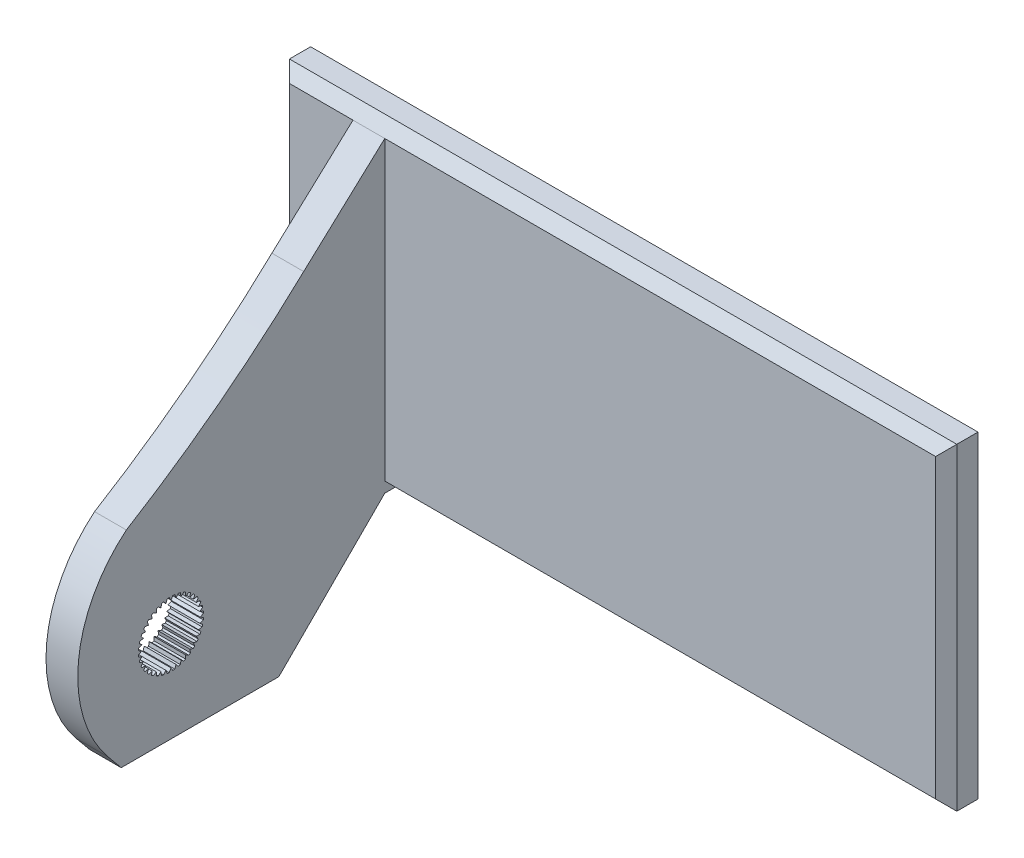
SolidWorks part; units mm, degrees
ref_plane "Front Plane" through (0, 0, 0) normal (0, 0, 1) x (1, 0, 0)
ref_plane "Top Plane" through (0, 0, 0) normal (0, 1, 0) x (1, 0, 0)
ref_plane "Right Plane" through (0, 0, 0) normal (1, 0, 0) x (0, 0, -1)
sketch "Sketch2" plane through (0, 0, 0) normal (0, 0, 1) x (1, 0, 0)
  line L1 (-31.5, -15) -> (31.5, -15)
  line L2 (-31.5, -15) -> (-31.5, 15)
  line L3 (-31.5, 15) -> (31.5, 15)
  line L4 (31.5, -15) -> (31.5, 15)
  point P4 (0, 15)
  point P6 (-31.5, 0)
  dimension "D1" = 63
  dimension "D2" = 30
extrude "Boss-Extrude2" add sketch "Sketch2" along normal blind 3
sketch "Sketch6" plane through (0, 0, 3) normal (0, 0, 1) x (1, 0, 0)
  line L0 (31.5, 15) -> (-31.5, 15) construction
  line L1 (-24.5, 15) -> (-21.5, 15)
  line L2 (-24.5, 15) -> (-24.5, -15)
  line L3 (-24.5, -15) -> (-21.5, -15)
  line L4 (-21.5, 15) -> (-21.5, -15)
  line L5 (-31.5, -15) -> (31.5, -15) construction
  line L6 (-31.5, 15) -> (-31.5, -15) construction
  dimension "D1" = 3
  dimension "D2" = 7
extrude "Boss-Extrude5" add sketch "Sketch6" along normal blind 20
sketch "Sketch7" plane through (0, -15, 0) normal (0, -1, 0) x (1, 0, 0)
  line L0 (-31.5, 0) -> (31.5, 0) construction
  line L1 (-24.5, 23) -> (-21.5, 23)
  line L2 (-24.5, 23) -> (-24.5, 0)
  line L3 (-24.5, 0) -> (-21.5, 0)
  line L4 (-21.5, 23) -> (-21.5, 0)
  dimension "D1" = 3
extrude "Boss-Extrude6" add sketch "Sketch7" along normal blind 10
sketch "Sketch8" plane through (0, 0, 23) normal (0, 0, 1) x (1, 0, 0)
  line L6 (-24.5, 15) -> (-24.5, -25)
  line L7 (-24.5, -25) -> (-21.5, -25)
  line L8 (-21.5, -25) -> (-21.5, 15)
  line L11 (-21.5, 15) -> (-24.5, 15)
  line L12 (-24.5, 15) -> (-24.5, -25)
  line L13 (-24.5, -25) -> (-21.5, -25)
  line L14 (-21.5, -25) -> (-21.5, 15)
  line L17 (-21.5, 15) -> (-24.5, 15)
  dimension "D1" = 0
extrude "Boss-Extrude7" add sketch "Sketch8" along normal blind 15
sketch "Sketch9" plane through (-24.5, 0, 0) normal (-1, 0, 0) x (0, 0, 1)
  line L288 (25.551, -14.882) -> (25.5973, -14.8018) construction
  line L289 (25.5298, -14.7054) -> (25.4386, -14.7215) construction
  line L290 (25.5973, -14.8018) -> (25.6299, -14.7454) construction
  line L291 (25.5939, -14.6941) -> (25.5298, -14.7054) construction
  line L292 (25.4711, -15.0204) -> (25.551, -14.882) construction
  line L293 (25.4386, -14.7215) -> (25.2812, -14.7493) construction
  line L294 (25.279, -14.4066) -> (25.3013, -14.3454) construction
  line L295 (25.257, -14.3011) -> (25.1958, -14.3233) construction
  line L296 (25.2473, -14.4936) -> (25.279, -14.4066) construction
  line L297 (25.1958, -14.3233) -> (25.1088, -14.355) construction
  line L298 (25.1927, -14.6438) -> (25.2473, -14.4936) construction
  line L299 (25.1088, -14.355) -> (24.9586, -14.4097) construction
  line L300 (24.8569, -13.9725) -> (24.8005, -14.0051) construction
  line L301 (24.8969, -14.0726) -> (24.9082, -14.0084) construction
  line L302 (24.8005, -14.0051) -> (24.7203, -14.0514) construction
  line L303 (24.8808, -14.1638) -> (24.8969, -14.0726) construction
  line L304 (24.7203, -14.0514) -> (24.5819, -14.1313) construction
  line L305 (24.8531, -14.3211) -> (24.8808, -14.1638) construction
  line L306 (25.6799, -15.4397) -> (25.7826, -15.3173) construction
  line L307 (25.6998, -15.1397) -> (25.54, -15.1397) construction
  line L308 (25.8421, -15.2464) -> (25.884, -15.1965) construction
  line L309 (25.8575, -15.1397) -> (25.7924, -15.1397) construction
  line L310 (25.7826, -15.3173) -> (25.8421, -15.2464) construction
  line L311 (25.7924, -15.1397) -> (25.6998, -15.1397) construction
  line L312 (26.006, -15.7267) -> (26.0559, -15.6848) construction
  line L313 (26.0397, -15.6243) -> (25.9756, -15.613) construction
  line L314 (25.9351, -15.7862) -> (26.006, -15.7267) construction
  line L315 (25.9756, -15.613) -> (25.8843, -15.5969) construction
  line L316 (25.8126, -15.8889) -> (25.9351, -15.7862) construction
  line L317 (25.8843, -15.5969) -> (25.727, -15.5692) construction
  line L318 (25.8654, -16.3543) -> (26.0038, -16.2744) construction
  line L319 (25.9867, -16.0792) -> (25.8366, -16.0246) construction
  line L320 (26.0038, -16.2744) -> (26.084, -16.2281) construction
  line L321 (26.0738, -16.1109) -> (25.9867, -16.0792) construction
  line L322 (26.084, -16.2281) -> (26.1404, -16.1956) construction
  line L323 (26.1349, -16.1332) -> (26.0738, -16.1109) construction
  line L324 (26.1404, -16.6509) -> (26.084, -16.6183) construction
  line L325 (26.0738, -16.7355) -> (26.1349, -16.7133) construction
  line L326 (26.084, -16.6183) -> (26.0038, -16.572) construction
  line L327 (25.9867, -16.7672) -> (26.0738, -16.7355) construction
  line L328 (26.0038, -16.572) -> (25.8654, -16.4921) construction
  line L329 (25.8366, -16.8219) -> (25.9867, -16.7672) construction
  line L330 (25.9756, -17.2334) -> (26.0397, -17.2221) construction
  line L331 (26.0559, -17.1616) -> (26.006, -17.1198) construction
  line L332 (25.8843, -17.2495) -> (25.9756, -17.2334) construction
  line L333 (26.006, -17.1198) -> (25.9351, -17.0602) construction
  line L334 (25.727, -17.2773) -> (25.8843, -17.2495) construction
  line L335 (25.9351, -17.0602) -> (25.8126, -16.9575) construction
  line L336 (25.6998, -17.7067) -> (25.7924, -17.7067) construction
  line L337 (25.8421, -17.6001) -> (25.7826, -17.5291) construction
  line L338 (25.54, -17.7067) -> (25.6998, -17.7067) construction
  line L339 (25.7826, -17.5291) -> (25.6799, -17.4067) construction
  line L340 (25.8654, -16.4921) -> (25.7461, -16.4232) construction
  line L341 (25.7461, -16.4232) -> (25.8654, -16.3543) construction
  line L342 (25.8366, -16.0246) -> (25.7071, -15.9775) construction
  line L343 (25.7071, -15.9775) -> (25.8126, -15.8889) construction
  line L344 (25.727, -15.5692) -> (25.5913, -15.5453) construction
  line L345 (25.5913, -15.5453) -> (25.6799, -15.4397) construction
  line L346 (25.54, -15.1397) -> (25.4022, -15.1397) construction
  line L347 (25.4022, -15.1397) -> (25.4711, -15.0204) construction
  line L348 (25.2812, -14.7493) -> (25.1456, -14.7732) construction
  line L349 (25.1456, -14.7732) -> (25.1927, -14.6438) construction
  line L350 (24.9586, -14.4097) -> (24.8292, -14.4568) construction
  line L351 (24.8292, -14.4568) -> (24.8531, -14.3211) construction
  line L352 (24.5819, -14.1313) -> (24.4626, -14.2001) construction
  line L353 (24.4626, -14.2001) -> (24.4626, -14.0624) construction
  line L354 (24.1626, -13.9225) -> (24.0571, -14.011) construction
  line L355 (24.0571, -14.011) -> (24.0332, -13.8754) construction
  line L356 (23.7134, -13.7897) -> (23.6249, -13.8952) construction
  line L357 (23.6249, -13.8952) -> (23.5778, -13.7658) construction
  line L358 (23.248, -13.7369) -> (23.1791, -13.8562) construction
  line L359 (23.1791, -13.8562) -> (23.1103, -13.7369) construction
  line L360 (22.7805, -13.7658) -> (22.7334, -13.8952) construction
  line L361 (22.7334, -13.8952) -> (22.6449, -13.7897) construction
  line L362 (22.3251, -13.8754) -> (22.3012, -14.011) construction
  line L363 (22.3012, -14.011) -> (22.1957, -13.9225) construction
  line L364 (21.8957, -14.0624) -> (21.8957, -14.2001) construction
  line L365 (21.8957, -14.2001) -> (21.7764, -14.1313) construction
  line L366 (21.5052, -14.3211) -> (21.5291, -14.4568) construction
  line L367 (21.5291, -14.4568) -> (21.3997, -14.4097) construction
  line L368 (21.1656, -14.6438) -> (21.2127, -14.7732) construction
  line L369 (21.2127, -14.7732) -> (21.0771, -14.7493) construction
  line L370 (20.8872, -15.0204) -> (20.9561, -15.1397) construction
  line L371 (20.9561, -15.1397) -> (20.8183, -15.1397) construction
  line L372 (20.6784, -15.4397) -> (20.767, -15.5453) construction
  line L373 (20.767, -15.5453) -> (20.6313, -15.5692) construction
  line L374 (20.5456, -15.8889) -> (20.6512, -15.9775) construction
  line L375 (20.6512, -15.9775) -> (20.5217, -16.0246) construction
  line L376 (20.4929, -16.3543) -> (20.6122, -16.4232) construction
  line L377 (20.6122, -16.4232) -> (20.4929, -16.4921) construction
  line L378 (20.5217, -16.8219) -> (20.6512, -16.869) construction
  line L379 (20.6512, -16.869) -> (20.5456, -16.9575) construction
  line L380 (20.6313, -17.2773) -> (20.767, -17.3012) construction
  line L381 (20.767, -17.3012) -> (20.6784, -17.4067) construction
  line L382 (20.8183, -17.7067) -> (20.9561, -17.7067) construction
  line L383 (20.9561, -17.7067) -> (20.8872, -17.826) construction
  line L384 (21.0771, -18.0972) -> (21.2127, -18.0732) construction
  line L385 (21.2127, -18.0732) -> (21.1656, -18.2027) construction
  line L386 (21.3997, -18.4368) -> (21.5291, -18.3896) construction
  line L387 (21.5291, -18.3896) -> (21.5052, -18.5253) construction
  line L388 (21.7764, -18.7152) -> (21.8957, -18.6463) construction
  line L389 (21.8957, -18.6463) -> (21.8957, -18.784) construction
  line L390 (22.1957, -18.9239) -> (22.3012, -18.8354) construction
  line L391 (22.3012, -18.8354) -> (22.3251, -18.971) construction
  line L392 (22.6449, -19.0567) -> (22.7334, -18.9512) construction
  line L393 (22.7334, -18.9512) -> (22.7805, -19.0806) construction
  line L394 (23.1103, -19.1095) -> (23.1791, -18.9902) construction
  line L395 (23.1791, -18.9902) -> (23.248, -19.1095) construction
  line L396 (23.5778, -19.0806) -> (23.6249, -18.9512) construction
  line L397 (23.6249, -18.9512) -> (23.7134, -19.0567) construction
  line L398 (24.0332, -18.971) -> (24.0571, -18.8354) construction
  line L399 (24.0571, -18.8354) -> (24.1626, -18.9239) construction
  line L400 (24.4626, -18.784) -> (24.4626, -18.6463) construction
  line L401 (24.4626, -18.6463) -> (24.5819, -18.7152) construction
  line L402 (24.8531, -18.5253) -> (24.8292, -18.3896) construction
  line L403 (24.8292, -18.3896) -> (24.9586, -18.4368) construction
  line L404 (25.1927, -18.2027) -> (25.1456, -18.0732) construction
  line L405 (25.1456, -18.0732) -> (25.2812, -18.0972) construction
  line L406 (25.4711, -17.826) -> (25.4022, -17.7067) construction
  line L407 (25.4022, -17.7067) -> (25.54, -17.7067) construction
  line L408 (25.6799, -17.4067) -> (25.5913, -17.3012) construction
  line L409 (25.5913, -17.3012) -> (25.727, -17.2773) construction
  line L410 (25.8126, -16.9575) -> (25.7071, -16.869) construction
  line L411 (25.7071, -16.869) -> (25.8366, -16.8219) construction
  line L412 (25.7924, -17.7067) -> (25.8575, -17.7067) construction
  line L413 (25.884, -17.6499) -> (25.8421, -17.6001) construction
  line L414 (25.6299, -18.101) -> (25.5973, -18.0446) construction
  line L415 (25.5298, -18.141) -> (25.5939, -18.1523) construction
  line L416 (25.5973, -18.0446) -> (25.551, -17.9644) construction
  line L417 (25.4386, -18.1249) -> (25.5298, -18.141) construction
  line L418 (24.9586, -18.4368) -> (25.1088, -18.4914) construction
  line L419 (25.2473, -18.3528) -> (25.1927, -18.2027) construction
  line L420 (25.1088, -18.4914) -> (25.1958, -18.5231) construction
  line L421 (25.279, -18.4399) -> (25.2473, -18.3528) construction
  line L422 (25.1958, -18.5231) -> (25.257, -18.5454) construction
  line L423 (25.3013, -18.5011) -> (25.279, -18.4399) construction
  line L424 (25.551, -17.9644) -> (25.4711, -17.826) construction
  line L425 (25.2812, -18.0972) -> (25.4386, -18.1249) construction
  line L426 (24.9082, -18.838) -> (24.8969, -18.7739) construction
  line L427 (24.8005, -18.8414) -> (24.8569, -18.8739) construction
  line L428 (24.8969, -18.7739) -> (24.8808, -18.6827) construction
  line L429 (24.7203, -18.7951) -> (24.8005, -18.8414) construction
  line L430 (24.8808, -18.6827) -> (24.8531, -18.5253) construction
  line L431 (24.5819, -18.7152) -> (24.7203, -18.7951) construction
  line L432 (22.8668, -19.3178) -> (22.8891, -19.379) construction
  line L433 (22.9515, -19.3845) -> (22.9841, -19.3281) construction
  line L434 (22.8352, -19.2308) -> (22.8668, -19.3178) construction
  line L435 (22.9841, -19.3281) -> (23.0304, -19.2479) construction
  line L436 (23.5231, -19.2308) -> (23.5778, -19.0806) construction
  line L437 (23.248, -19.1095) -> (23.3279, -19.2479) construction
  line L438 (23.4915, -19.3178) -> (23.5231, -19.2308) construction
  line L439 (23.3279, -19.2479) -> (23.3742, -19.3281) construction
  line L440 (23.4692, -19.379) -> (23.4915, -19.3178) construction
  line L441 (23.3742, -19.3281) -> (23.4068, -19.3845) construction
  line L442 (23.8757, -19.2501) -> (23.9175, -19.3) construction
  line L443 (23.978, -19.2838) -> (23.9894, -19.2196) construction
  line L444 (24.356, -19.0862) -> (24.4059, -19.128) construction
  line L445 (24.4626, -19.1016) -> (24.4626, -19.0365) construction
  line L446 (24.285, -19.0267) -> (24.356, -19.0862) construction
  line L447 (24.4626, -19.0365) -> (24.4626, -18.9438) construction
  line L448 (24.1626, -18.9239) -> (24.285, -19.0267) construction
  line L449 (24.4626, -18.9438) -> (24.4626, -18.784) construction
  line L450 (23.8162, -19.1791) -> (23.8757, -19.2501) construction
  line L451 (23.9894, -19.2196) -> (24.0054, -19.1284) construction
  line L452 (23.7134, -19.0567) -> (23.8162, -19.1791) construction
  line L453 (24.0054, -19.1284) -> (24.0332, -18.971) construction
  line L454 (22.7805, -19.0806) -> (22.8352, -19.2308) construction
  line L455 (23.0304, -19.2479) -> (23.1103, -19.1095) construction
  line L456 (22.3689, -19.2196) -> (22.3802, -19.2838) construction
  line L457 (22.4407, -19.3) -> (22.4826, -19.2501) construction
  line L458 (22.3529, -19.1284) -> (22.3689, -19.2196) construction
  line L459 (22.4826, -19.2501) -> (22.5421, -19.1791) construction
  line L460 (22.3251, -18.971) -> (22.3529, -19.1284) construction
  line L461 (22.5421, -19.1791) -> (22.6449, -19.0567) construction
  line L462 (21.8957, -19.0365) -> (21.8957, -19.1016) construction
  line L463 (21.9524, -19.128) -> (22.0023, -19.0862) construction
  line L464 (21.8957, -18.9438) -> (21.8957, -19.0365) construction
  line L465 (22.0023, -19.0862) -> (22.0733, -19.0267) construction
  line L466 (21.8957, -18.784) -> (21.8957, -18.9438) construction
  line L467 (22.0733, -19.0267) -> (22.1957, -18.9239) construction
  line L468 (21.4614, -18.7739) -> (21.4501, -18.838) construction
  line L469 (21.5014, -18.8739) -> (21.5578, -18.8414) construction
  line L470 (21.4775, -18.6827) -> (21.4614, -18.7739) construction
  line L471 (21.5578, -18.8414) -> (21.638, -18.7951) construction
  line L472 (21.5052, -18.5253) -> (21.4775, -18.6827) construction
  line L473 (21.638, -18.7951) -> (21.7764, -18.7152) construction
  line L474 (21.0793, -18.4399) -> (21.057, -18.5011) construction
  line L475 (21.1013, -18.5454) -> (21.1625, -18.5231) construction
  line L476 (21.111, -18.3528) -> (21.0793, -18.4399) construction
  line L477 (21.1625, -18.5231) -> (21.2495, -18.4914) construction
  line L478 (21.1656, -18.2027) -> (21.111, -18.3528) construction
  line L479 (21.2495, -18.4914) -> (21.3997, -18.4368) construction
  line L480 (20.7644, -18.1523) -> (20.8285, -18.141) construction
  line L481 (20.761, -18.0446) -> (20.7284, -18.101) construction
  line L482 (20.8285, -18.141) -> (20.9197, -18.1249) construction
  line L483 (20.8073, -17.9644) -> (20.761, -18.0446) construction
  line L484 (20.9197, -18.1249) -> (21.0771, -18.0972) construction
  line L485 (20.8872, -17.826) -> (20.8073, -17.9644) construction
  line L486 (20.5008, -17.7067) -> (20.5659, -17.7067) construction
  line L487 (20.5162, -17.6001) -> (20.4743, -17.6499) construction
  line L488 (20.5659, -17.7067) -> (20.6585, -17.7067) construction
  line L489 (20.5757, -17.5291) -> (20.5162, -17.6001) construction
  line L490 (20.6585, -17.7067) -> (20.8183, -17.7067) construction
  line L491 (20.6784, -17.4067) -> (20.5757, -17.5291) construction
  line L492 (20.3186, -17.2221) -> (20.3827, -17.2334) construction
  line L493 (20.3523, -17.1198) -> (20.3024, -17.1616) construction
  line L494 (20.3827, -17.2334) -> (20.4739, -17.2495) construction
  line L495 (20.4232, -17.0602) -> (20.3523, -17.1198) construction
  line L496 (20.4739, -17.2495) -> (20.6313, -17.2773) construction
  line L497 (20.5456, -16.9575) -> (20.4232, -17.0602) construction
  line L498 (20.2233, -16.7133) -> (20.2845, -16.7355) construction
  line L499 (20.2743, -16.6183) -> (20.2179, -16.6509) construction
  line L500 (20.3716, -16.7672) -> (20.5217, -16.8219) construction
  line L501 (20.4929, -16.4921) -> (20.3545, -16.572) construction
  line L502 (20.2845, -16.7355) -> (20.3716, -16.7672) construction
  line L503 (20.3545, -16.572) -> (20.2743, -16.6183) construction
  line L504 (20.2179, -16.1956) -> (20.2743, -16.2281) construction
  line L505 (20.2845, -16.1109) -> (20.2233, -16.1332) construction
  line L506 (20.2743, -16.2281) -> (20.3545, -16.2744) construction
  line L507 (20.3716, -16.0792) -> (20.2845, -16.1109) construction
  line L508 (20.3545, -16.2744) -> (20.4929, -16.3543) construction
  line L509 (20.5217, -16.0246) -> (20.3716, -16.0792) construction
  line L510 (20.3523, -15.7267) -> (20.4232, -15.7862) construction
  line L511 (20.4739, -15.5969) -> (20.3827, -15.613) construction
  line L512 (20.3024, -15.6848) -> (20.3523, -15.7267) construction
  line L513 (20.3827, -15.613) -> (20.3186, -15.6243) construction
  line L514 (20.4232, -15.7862) -> (20.5456, -15.8889) construction
  line L515 (20.6313, -15.5692) -> (20.4739, -15.5969) construction
  line L516 (20.5162, -15.2464) -> (20.5757, -15.3173) construction
  line L517 (20.6585, -15.1397) -> (20.5659, -15.1397) construction
  line L518 (20.4743, -15.1965) -> (20.5162, -15.2464) construction
  line L519 (20.5659, -15.1397) -> (20.5008, -15.1397) construction
  line L520 (20.5757, -15.3173) -> (20.6784, -15.4397) construction
  line L521 (20.8183, -15.1397) -> (20.6585, -15.1397) construction
  line L522 (20.7284, -14.7454) -> (20.761, -14.8018) construction
  line L523 (20.8285, -14.7054) -> (20.7644, -14.6941) construction
  line L524 (20.761, -14.8018) -> (20.8073, -14.882) construction
  line L525 (20.9197, -14.7215) -> (20.8285, -14.7054) construction
  line L526 (20.8073, -14.882) -> (20.8872, -15.0204) construction
  line L527 (21.0771, -14.7493) -> (20.9197, -14.7215) construction
  line L528 (21.1625, -14.3233) -> (21.1013, -14.3011) construction
  line L529 (21.057, -14.3454) -> (21.0793, -14.4066) construction
  line L530 (21.2495, -14.355) -> (21.1625, -14.3233) construction
  line L531 (21.0793, -14.4066) -> (21.111, -14.4936) construction
  line L532 (21.3997, -14.4097) -> (21.2495, -14.355) construction
  line L533 (21.111, -14.4936) -> (21.1656, -14.6438) construction
  line L534 (21.4501, -14.0084) -> (21.4614, -14.0726) construction
  line L535 (21.5578, -14.0051) -> (21.5014, -13.9725) construction
  line L536 (21.4614, -14.0726) -> (21.4775, -14.1638) construction
  line L537 (21.638, -14.0514) -> (21.5578, -14.0051) construction
  line L538 (21.4775, -14.1638) -> (21.5052, -14.3211) construction
  line L539 (21.7764, -14.1313) -> (21.638, -14.0514) construction
  line L540 (21.8957, -13.7449) -> (21.8957, -13.81) construction
  line L541 (22.0023, -13.7602) -> (21.9524, -13.7184) construction
  line L542 (21.8957, -13.81) -> (21.8957, -13.9026) construction
  line L543 (22.0733, -13.8198) -> (22.0023, -13.7602) construction
  line L544 (21.8957, -13.9026) -> (21.8957, -14.0624) construction
  line L545 (22.1957, -13.9225) -> (22.0733, -13.8198) construction
  line L546 (22.3802, -13.5627) -> (22.3689, -13.6268) construction
  line L547 (22.4826, -13.5963) -> (22.4407, -13.5465) construction
  line L548 (22.3689, -13.6268) -> (22.3529, -13.718) construction
  line L549 (22.5421, -13.6673) -> (22.4826, -13.5963) construction
  line L550 (22.3529, -13.718) -> (22.3251, -13.8754) construction
  line L551 (22.6449, -13.7897) -> (22.5421, -13.6673) construction
  line L552 (24.356, -13.7602) -> (24.285, -13.8198) construction
  line L553 (24.4626, -13.9026) -> (24.4626, -13.81) construction
  line L554 (24.4059, -13.7184) -> (24.356, -13.7602) construction
  line L555 (24.4626, -13.81) -> (24.4626, -13.7449) construction
  line L556 (24.285, -13.8198) -> (24.1626, -13.9225) construction
  line L557 (24.4626, -14.0624) -> (24.4626, -13.9026) construction
  line L558 (23.9894, -13.6268) -> (23.978, -13.5627) construction
  line L559 (23.9175, -13.5465) -> (23.8757, -13.5963) construction
  line L560 (24.0054, -13.718) -> (23.9894, -13.6268) construction
  line L561 (23.8757, -13.5963) -> (23.8162, -13.6673) construction
  line L562 (24.0332, -13.8754) -> (24.0054, -13.718) construction
  line L563 (23.8162, -13.6673) -> (23.7134, -13.7897) construction
  line L564 (23.4915, -13.5286) -> (23.4692, -13.4674) construction
  line L565 (23.4068, -13.462) -> (23.3742, -13.5183) construction
  line L566 (23.5231, -13.6156) -> (23.4915, -13.5286) construction
  line L567 (23.3742, -13.5183) -> (23.3279, -13.5986) construction
  line L568 (23.5778, -13.7658) -> (23.5231, -13.6156) construction
  line L569 (23.3279, -13.5986) -> (23.248, -13.7369) construction
  line L570 (22.8891, -13.4674) -> (22.8668, -13.5286) construction
  line L571 (22.9841, -13.5183) -> (22.9515, -13.462) construction
  line L572 (22.8668, -13.5286) -> (22.8352, -13.6156) construction
  line L573 (23.0304, -13.5986) -> (22.9841, -13.5183) construction
  line L574 (22.8352, -13.6156) -> (22.7805, -13.7658) construction
  line L575 (23.1103, -13.7369) -> (23.0304, -13.5986) construction
  line L576 (25.6376, -14.932) -> (25.6839, -14.8518)
  line L577 (25.6839, -14.8518) -> (25.7476, -14.7415)
  line L578 (25.6379, -14.5848) -> (25.5124, -14.607)
  line L579 (25.5124, -14.607) -> (25.4212, -14.623)
  line L580 (25.4212, -14.623) -> (25.2988, -14.6446)
  line L581 (25.2988, -14.6446) -> (25.3413, -14.5278)
  line L582 (25.3413, -14.5278) -> (25.373, -14.4408)
  line L583 (25.373, -14.4408) -> (25.4165, -14.3211)
  line L584 (25.2813, -14.1858) -> (25.1616, -14.2294)
  line L585 (25.1616, -14.2294) -> (25.0746, -14.2611)
  line L586 (25.0746, -14.2611) -> (24.9577, -14.3036)
  line L587 (24.9577, -14.3036) -> (24.9793, -14.1811)
  line L588 (24.9793, -14.1811) -> (24.9954, -14.0899)
  line L589 (24.9954, -14.0899) -> (25.0175, -13.9645)
  line L590 (24.8608, -13.8548) -> (24.7505, -13.9185)
  line L591 (24.7505, -13.9185) -> (24.6703, -13.9648)
  line L592 (24.6703, -13.9648) -> (24.5626, -14.0269)
  line L593 (24.5626, -14.0269) -> (24.5626, -13.9026)
  line L594 (24.5626, -13.9026) -> (24.5626, -13.81)
  line L595 (24.5626, -13.81) -> (24.5626, -13.6826)
  line L596 (24.3893, -13.6018) -> (24.2917, -13.6836)
  line L597 (24.2917, -13.6836) -> (24.2208, -13.7432)
  line L598 (24.2208, -13.7432) -> (24.1255, -13.8231)
  line L599 (24.1255, -13.8231) -> (24.1039, -13.7007)
  line L600 (24.1039, -13.7007) -> (24.0878, -13.6094)
  line L601 (24.0878, -13.6094) -> (24.0657, -13.484)
  line L602 (23.8809, -13.4345) -> (23.7991, -13.5321)
  line L603 (23.7991, -13.5321) -> (23.7395, -13.603)
  line L604 (23.7395, -13.603) -> (23.6596, -13.6983)
  line L605 (23.6596, -13.6983) -> (23.6171, -13.5814)
  line L606 (23.6171, -13.5814) -> (23.5854, -13.4944)
  line L607 (23.5854, -13.4944) -> (23.5419, -13.3747)
  line L608 (23.3513, -13.358) -> (23.2876, -13.4683)
  line L609 (23.2876, -13.4683) -> (23.2413, -13.5486)
  line L610 (23.2413, -13.5486) -> (23.1791, -13.6562)
  line L611 (23.1791, -13.6562) -> (23.117, -13.5486)
  line L612 (23.117, -13.5486) -> (23.0707, -13.4683)
  line L613 (23.0707, -13.4683) -> (23.007, -13.358)
  line L614 (22.8164, -13.3747) -> (22.7729, -13.4944)
  line L615 (22.7729, -13.4944) -> (22.7412, -13.5814)
  line L616 (22.7412, -13.5814) -> (22.6987, -13.6983)
  line L617 (22.6987, -13.6983) -> (22.6187, -13.603)
  line L618 (22.6187, -13.603) -> (22.5592, -13.5321)
  line L619 (22.5592, -13.5321) -> (22.4773, -13.4345)
  line L620 (22.2926, -13.484) -> (22.2705, -13.6094)
  line L621 (22.2705, -13.6094) -> (22.2544, -13.7007)
  line L622 (22.2544, -13.7007) -> (22.2328, -13.8231)
  line L623 (22.2328, -13.8231) -> (22.1375, -13.7432)
  line L624 (22.1375, -13.7432) -> (22.0666, -13.6836)
  line L625 (22.0666, -13.6836) -> (21.969, -13.6018)
  line L626 (21.7957, -13.6826) -> (21.7957, -13.81)
  line L627 (21.7957, -13.81) -> (21.7957, -13.9026)
  line L628 (21.7957, -13.9026) -> (21.7957, -14.0269)
  line L629 (21.7957, -14.0269) -> (21.688, -13.9648)
  line L630 (21.688, -13.9648) -> (21.6078, -13.9185)
  line L631 (21.6078, -13.9185) -> (21.4975, -13.8548)
  line L632 (21.3408, -13.9645) -> (21.3629, -14.0899)
  line L633 (21.3629, -14.0899) -> (21.379, -14.1811)
  line L634 (21.379, -14.1811) -> (21.4006, -14.3036)
  line L635 (21.4006, -14.3036) -> (21.2837, -14.2611)
  line L636 (21.2837, -14.2611) -> (21.1967, -14.2294)
  line L637 (21.1967, -14.2294) -> (21.077, -14.1858)
  line L638 (20.9417, -14.3211) -> (20.9853, -14.4408)
  line L639 (20.9853, -14.4408) -> (21.017, -14.5278)
  line L640 (21.017, -14.5278) -> (21.0595, -14.6446)
  line L641 (21.0595, -14.6446) -> (20.9371, -14.623)
  line L642 (20.9371, -14.623) -> (20.8458, -14.607)
  line L643 (20.8458, -14.607) -> (20.7204, -14.5848)
  line L644 (20.6107, -14.7415) -> (20.6744, -14.8518)
  line L645 (20.6744, -14.8518) -> (20.7207, -14.932)
  line L646 (20.7207, -14.932) -> (20.7829, -15.0397)
  line L647 (20.7829, -15.0397) -> (20.6585, -15.0397)
  line L648 (20.6585, -15.0397) -> (20.5659, -15.0397)
  line L649 (20.5659, -15.0397) -> (20.4386, -15.0397)
  line L650 (20.3577, -15.2131) -> (20.4396, -15.3107)
  line L651 (20.4396, -15.3107) -> (20.4991, -15.3816)
  line L652 (20.4991, -15.3816) -> (20.579, -15.4769)
  line L653 (20.579, -15.4769) -> (20.4566, -15.4984)
  line L654 (20.4566, -15.4984) -> (20.3654, -15.5145)
  line L655 (20.3654, -15.5145) -> (20.2399, -15.5366)
  line L656 (20.1904, -15.7214) -> (20.288, -15.8033)
  line L657 (20.288, -15.8033) -> (20.3589, -15.8628)
  line L658 (20.3589, -15.8628) -> (20.4542, -15.9427)
  line L659 (20.4542, -15.9427) -> (20.3374, -15.9853)
  line L660 (20.3374, -15.9853) -> (20.2503, -16.0169)
  line L661 (20.2503, -16.0169) -> (20.1306, -16.0605)
  line L662 (20.114, -16.2511) -> (20.2243, -16.3147)
  line L663 (20.2243, -16.3147) -> (20.3045, -16.3611)
  line L664 (20.3045, -16.3611) -> (20.4122, -16.4232)
  line L665 (20.4122, -16.4232) -> (20.3045, -16.4854)
  line L666 (20.3045, -16.4854) -> (20.2243, -16.5317)
  line L667 (20.2243, -16.5317) -> (20.114, -16.5954)
  line L668 (20.1306, -16.7859) -> (20.2503, -16.8295)
  line L669 (20.2503, -16.8295) -> (20.3374, -16.8612)
  line L670 (20.3374, -16.8612) -> (20.4542, -16.9037)
  line L671 (20.4542, -16.9037) -> (20.3589, -16.9836)
  line L672 (20.3589, -16.9836) -> (20.288, -17.0432)
  line L673 (20.288, -17.0432) -> (20.1904, -17.125)
  line L674 (20.2399, -17.3098) -> (20.3654, -17.3319)
  line L675 (20.3654, -17.3319) -> (20.4566, -17.348)
  line L676 (20.4566, -17.348) -> (20.579, -17.3696)
  line L677 (20.579, -17.3696) -> (20.4991, -17.4648)
  line L678 (20.4991, -17.4648) -> (20.4396, -17.5358)
  line L679 (20.4396, -17.5358) -> (20.3577, -17.6333)
  line L680 (20.4386, -17.8067) -> (20.5659, -17.8067)
  line L681 (20.5659, -17.8067) -> (20.6585, -17.8067)
  line L682 (20.6585, -17.8067) -> (20.7829, -17.8067)
  line L683 (20.7829, -17.8067) -> (20.7207, -17.9144)
  line L684 (20.7207, -17.9144) -> (20.6744, -17.9946)
  line L685 (20.6744, -17.9946) -> (20.6107, -18.1049)
  line L686 (20.7204, -18.2616) -> (20.8458, -18.2395)
  line L687 (20.8458, -18.2395) -> (20.9371, -18.2234)
  line L688 (20.9371, -18.2234) -> (21.0595, -18.2018)
  line L689 (21.0595, -18.2018) -> (21.017, -18.3186)
  line L690 (21.017, -18.3186) -> (20.9853, -18.4057)
  line L691 (20.9853, -18.4057) -> (20.9417, -18.5253)
  line L692 (21.077, -18.6606) -> (21.1967, -18.6171)
  line L693 (21.1967, -18.6171) -> (21.2837, -18.5854)
  line L694 (21.2837, -18.5854) -> (21.4006, -18.5429)
  line L695 (21.4006, -18.5429) -> (21.379, -18.6653)
  line L696 (21.379, -18.6653) -> (21.3629, -18.7565)
  line L697 (21.3629, -18.7565) -> (21.3408, -18.8819)
  line L698 (21.4975, -18.9917) -> (21.6078, -18.928)
  line L699 (21.6078, -18.928) -> (21.688, -18.8817)
  line L700 (21.688, -18.8817) -> (21.7957, -18.8195)
  line L701 (21.7957, -18.8195) -> (21.7957, -18.9438)
  line L702 (21.7957, -18.9438) -> (21.7957, -19.0365)
  line L703 (21.7957, -19.0365) -> (21.7957, -19.1638)
  line L704 (21.969, -19.2447) -> (22.0666, -19.1628)
  line L705 (22.0666, -19.1628) -> (22.1375, -19.1033)
  line L706 (22.1375, -19.1033) -> (22.2328, -19.0233)
  line L707 (22.2328, -19.0233) -> (22.2544, -19.1458)
  line L708 (22.2544, -19.1458) -> (22.2705, -19.237)
  line L709 (22.2705, -19.237) -> (22.2926, -19.3624)
  line L710 (22.4773, -19.4119) -> (22.5592, -19.3144)
  line L711 (22.5592, -19.3144) -> (22.6187, -19.2434)
  line L712 (22.6187, -19.2434) -> (22.6987, -19.1482)
  line L713 (22.6987, -19.1482) -> (22.7412, -19.265)
  line L714 (22.7412, -19.265) -> (22.7729, -19.352)
  line L715 (22.7729, -19.352) -> (22.8164, -19.4717)
  line L716 (23.007, -19.4884) -> (23.0707, -19.3781)
  line L717 (23.0707, -19.3781) -> (23.117, -19.2979)
  line L718 (23.117, -19.2979) -> (23.1791, -19.1902)
  line L719 (23.1791, -19.1902) -> (23.2413, -19.2979)
  line L720 (23.2413, -19.2979) -> (23.2876, -19.3781)
  line L721 (23.2876, -19.3781) -> (23.3513, -19.4884)
  line L722 (23.5419, -19.4717) -> (23.5854, -19.352)
  line L723 (23.5854, -19.352) -> (23.6171, -19.265)
  line L724 (23.6171, -19.265) -> (23.6596, -19.1482)
  line L725 (23.6596, -19.1482) -> (23.7395, -19.2434)
  line L726 (23.7395, -19.2434) -> (23.7991, -19.3144)
  line L727 (23.7991, -19.3144) -> (23.8809, -19.4119)
  line L728 (24.0657, -19.3624) -> (24.0878, -19.237)
  line L729 (24.0878, -19.237) -> (24.1039, -19.1458)
  line L730 (24.1039, -19.1458) -> (24.1255, -19.0233)
  line L731 (24.1255, -19.0233) -> (24.2208, -19.1033)
  line L732 (24.2208, -19.1033) -> (24.2917, -19.1628)
  line L733 (24.2917, -19.1628) -> (24.3893, -19.2447)
  line L734 (24.5626, -19.1638) -> (24.5626, -19.0365)
  line L735 (24.5626, -19.0365) -> (24.5626, -18.9438)
  line L736 (24.5626, -18.9438) -> (24.5626, -18.8195)
  line L737 (24.5626, -18.8195) -> (24.6703, -18.8817)
  line L738 (24.6703, -18.8817) -> (24.7505, -18.928)
  line L739 (24.7505, -18.928) -> (24.8608, -18.9917)
  line L740 (25.0175, -18.8819) -> (24.9954, -18.7565)
  line L741 (24.9954, -18.7565) -> (24.9793, -18.6653)
  line L742 (24.9793, -18.6653) -> (24.9577, -18.5429)
  line L743 (24.9577, -18.5429) -> (25.0746, -18.5854)
  line L744 (25.0746, -18.5854) -> (25.1616, -18.6171)
  line L745 (25.1616, -18.6171) -> (25.2813, -18.6606)
  line L746 (25.4165, -18.5253) -> (25.373, -18.4057)
  line L747 (25.373, -18.4057) -> (25.3413, -18.3186)
  line L748 (25.3413, -18.3186) -> (25.2988, -18.2018)
  line L749 (25.2988, -18.2018) -> (25.4212, -18.2234)
  line L750 (25.4212, -18.2234) -> (25.5124, -18.2395)
  line L751 (25.5124, -18.2395) -> (25.6379, -18.2616)
  line L752 (25.7476, -18.1049) -> (25.6839, -17.9946)
  line L753 (25.6839, -17.9946) -> (25.6376, -17.9144)
  line L754 (25.6376, -17.9144) -> (25.5754, -17.8067)
  line L755 (25.5754, -17.8067) -> (25.6998, -17.8067)
  line L756 (25.6998, -17.8067) -> (25.7924, -17.8067)
  line L757 (25.7924, -17.8067) -> (25.9197, -17.8067)
  line L758 (26.0006, -17.6333) -> (25.9187, -17.5358)
  line L759 (25.9187, -17.5358) -> (25.8592, -17.4648)
  line L760 (25.8592, -17.4648) -> (25.7793, -17.3696)
  line L761 (25.7793, -17.3696) -> (25.9017, -17.348)
  line L762 (25.9017, -17.348) -> (25.9929, -17.3319)
  line L763 (25.9929, -17.3319) -> (26.1183, -17.3098)
  line L764 (26.1679, -17.125) -> (26.0703, -17.0432)
  line L765 (26.0703, -17.0432) -> (25.9993, -16.9836)
  line L766 (25.9993, -16.9836) -> (25.9041, -16.9037)
  line L767 (25.9041, -16.9037) -> (26.0209, -16.8612)
  line L768 (26.0209, -16.8612) -> (26.108, -16.8295)
  line L769 (26.108, -16.8295) -> (26.2276, -16.7859)
  line L770 (26.2443, -16.5954) -> (26.134, -16.5317)
  line L771 (26.134, -16.5317) -> (26.0538, -16.4854)
  line L772 (26.0538, -16.4854) -> (25.9461, -16.4232)
  line L773 (25.9461, -16.4232) -> (26.0538, -16.3611)
  line L774 (26.0538, -16.3611) -> (26.134, -16.3147)
  line L775 (26.134, -16.3147) -> (26.2443, -16.2511)
  line L776 (26.2276, -16.0605) -> (26.108, -16.0169)
  line L777 (26.108, -16.0169) -> (26.0209, -15.9853)
  line L778 (26.0209, -15.9853) -> (25.9041, -15.9427)
  line L779 (25.9041, -15.9427) -> (25.9993, -15.8628)
  line L780 (25.9993, -15.8628) -> (26.0703, -15.8033)
  line L781 (26.0703, -15.8033) -> (26.1679, -15.7214)
  line L782 (26.1183, -15.5366) -> (25.9929, -15.5145)
  line L783 (25.9929, -15.5145) -> (25.9017, -15.4984)
  line L784 (25.9017, -15.4984) -> (25.7793, -15.4769)
  line L785 (25.7793, -15.4769) -> (25.8592, -15.3816)
  line L786 (25.8592, -15.3816) -> (25.9187, -15.3107)
  line L787 (25.9187, -15.3107) -> (26.0006, -15.2131)
  line L788 (25.9197, -15.0397) -> (25.7924, -15.0397)
  line L789 (25.7924, -15.0397) -> (25.6998, -15.0397)
  line L790 (25.6998, -15.0397) -> (25.5754, -15.0397)
  line L791 (25.5754, -15.0397) -> (25.6376, -14.932)
  arc A37 (25.6299, -14.7454) -> (25.5939, -14.6941) centre (23.1791, -16.4232) ccw construction
  arc A38 (25.3013, -14.3454) -> (25.257, -14.3011) centre (23.1791, -16.4232) ccw construction
  arc A39 (24.9082, -14.0084) -> (24.8569, -13.9725) centre (23.1791, -16.4232) ccw construction
  arc A40 (25.884, -15.1965) -> (25.8575, -15.1397) centre (23.1791, -16.4232) ccw construction
  arc A41 (26.0559, -15.6848) -> (26.0397, -15.6243) centre (23.1791, -16.4232) ccw construction
  arc A42 (26.1404, -16.1956) -> (26.1349, -16.1332) centre (23.1791, -16.4232) ccw construction
  arc A43 (26.1349, -16.7133) -> (26.1404, -16.6509) centre (23.1791, -16.4232) ccw construction
  arc A44 (26.0397, -17.2221) -> (26.0559, -17.1616) centre (23.1791, -16.4232) ccw construction
  arc A45 (25.8575, -17.7067) -> (25.884, -17.6499) centre (23.1791, -16.4232) ccw construction
  arc A46 (25.5939, -18.1523) -> (25.6299, -18.101) centre (23.1791, -16.4232) ccw construction
  arc A47 (25.257, -18.5454) -> (25.3013, -18.5011) centre (23.1791, -16.4232) ccw construction
  arc A48 (24.8569, -18.8739) -> (24.9082, -18.838) centre (23.1791, -16.4232) ccw construction
  arc A49 (22.8891, -19.379) -> (22.9515, -19.3845) centre (23.1791, -16.4232) ccw construction
  arc A50 (23.4068, -19.3845) -> (23.4692, -19.379) centre (23.1791, -16.4232) ccw construction
  arc A51 (23.9175, -19.3) -> (23.978, -19.2838) centre (23.1791, -16.4232) ccw construction
  arc A52 (24.4059, -19.128) -> (24.4626, -19.1016) centre (23.1791, -16.4232) ccw construction
  arc A53 (22.3802, -19.2838) -> (22.4407, -19.3) centre (23.1791, -16.4232) ccw construction
  arc A54 (21.8957, -19.1016) -> (21.9524, -19.128) centre (23.1791, -16.4232) ccw construction
  arc A55 (21.4501, -18.838) -> (21.5014, -18.8739) centre (23.1791, -16.4232) ccw construction
  arc A56 (21.057, -18.5011) -> (21.1013, -18.5454) centre (23.1791, -16.4232) ccw construction
  arc A57 (20.7284, -18.101) -> (20.7644, -18.1523) centre (23.1791, -16.4232) ccw construction
  arc A58 (20.4743, -17.6499) -> (20.5008, -17.7067) centre (23.1791, -16.4232) ccw construction
  arc A59 (20.3024, -17.1616) -> (20.3186, -17.2221) centre (23.1791, -16.4232) ccw construction
  arc A60 (20.2179, -16.6509) -> (20.2233, -16.7133) centre (23.1791, -16.4232) ccw construction
  arc A61 (20.2233, -16.1332) -> (20.2179, -16.1956) centre (23.1791, -16.4232) ccw construction
  arc A62 (20.3186, -15.6243) -> (20.3024, -15.6848) centre (23.1791, -16.4232) ccw construction
  arc A63 (20.5008, -15.1397) -> (20.4743, -15.1965) centre (23.1791, -16.4232) ccw construction
  arc A64 (20.7644, -14.6941) -> (20.7284, -14.7454) centre (23.1791, -16.4232) ccw construction
  arc A65 (21.1013, -14.3011) -> (21.057, -14.3454) centre (23.1791, -16.4232) ccw construction
  arc A66 (21.5014, -13.9725) -> (21.4501, -14.0084) centre (23.1791, -16.4232) ccw construction
  arc A67 (21.9524, -13.7184) -> (21.8957, -13.7449) centre (23.1791, -16.4232) ccw construction
  arc A68 (22.4407, -13.5465) -> (22.3802, -13.5627) centre (23.1791, -16.4232) ccw construction
  arc A69 (24.4626, -13.7449) -> (24.4059, -13.7184) centre (23.1791, -16.4232) ccw construction
  arc A70 (23.978, -13.5627) -> (23.9175, -13.5465) centre (23.1791, -16.4232) ccw construction
  arc A71 (23.4692, -13.4674) -> (23.4068, -13.462) centre (23.1791, -16.4232) ccw construction
  arc A72 (22.9515, -13.462) -> (22.8891, -13.4674) centre (23.1791, -16.4232) ccw construction
  arc A73 (25.7476, -14.7415) -> (25.6379, -14.5848) centre (23.1791, -16.4232) ccw
  arc A74 (25.4165, -14.3211) -> (25.2813, -14.1858) centre (23.1791, -16.4232) ccw
  arc A75 (25.0175, -13.9645) -> (24.8608, -13.8548) centre (23.1791, -16.4232) ccw
  arc A76 (24.5626, -13.6826) -> (24.3893, -13.6018) centre (23.1791, -16.4232) ccw
  arc A77 (24.0657, -13.484) -> (23.8809, -13.4345) centre (23.1791, -16.4232) ccw
  arc A78 (23.5419, -13.3747) -> (23.3513, -13.358) centre (23.1791, -16.4232) ccw
  arc A79 (23.007, -13.358) -> (22.8164, -13.3747) centre (23.1791, -16.4232) ccw
  arc A80 (22.4773, -13.4345) -> (22.2926, -13.484) centre (23.1791, -16.4232) ccw
  arc A81 (21.969, -13.6018) -> (21.7957, -13.6826) centre (23.1791, -16.4232) ccw
  arc A82 (21.4975, -13.8548) -> (21.3408, -13.9645) centre (23.1791, -16.4232) ccw
  arc A83 (21.077, -14.1858) -> (20.9417, -14.3211) centre (23.1791, -16.4232) ccw
  arc A84 (20.7204, -14.5848) -> (20.6107, -14.7415) centre (23.1791, -16.4232) ccw
  arc A85 (20.4386, -15.0397) -> (20.3577, -15.2131) centre (23.1791, -16.4232) ccw
  arc A86 (20.2399, -15.5366) -> (20.1904, -15.7214) centre (23.1791, -16.4232) ccw
  arc A87 (20.1306, -16.0605) -> (20.114, -16.2511) centre (23.1791, -16.4232) ccw
  arc A88 (20.114, -16.5954) -> (20.1306, -16.7859) centre (23.1791, -16.4232) ccw
  arc A89 (20.1904, -17.125) -> (20.2399, -17.3098) centre (23.1791, -16.4232) ccw
  arc A90 (20.3577, -17.6333) -> (20.4386, -17.8067) centre (23.1791, -16.4232) ccw
  arc A91 (20.6107, -18.1049) -> (20.7204, -18.2616) centre (23.1791, -16.4232) ccw
  arc A92 (20.9417, -18.5253) -> (21.077, -18.6606) centre (23.1791, -16.4232) ccw
  arc A93 (21.3408, -18.8819) -> (21.4975, -18.9917) centre (23.1791, -16.4232) ccw
  arc A94 (21.7957, -19.1638) -> (21.969, -19.2447) centre (23.1791, -16.4232) ccw
  arc A95 (22.2926, -19.3624) -> (22.4773, -19.4119) centre (23.1791, -16.4232) ccw
  arc A96 (22.8164, -19.4717) -> (23.007, -19.4884) centre (23.1791, -16.4232) ccw
  arc A97 (23.3513, -19.4884) -> (23.5419, -19.4717) centre (23.1791, -16.4232) ccw
  arc A98 (23.8809, -19.4119) -> (24.0657, -19.3624) centre (23.1791, -16.4232) ccw
  arc A99 (24.3893, -19.2447) -> (24.5626, -19.1638) centre (23.1791, -16.4232) ccw
  arc A100 (24.8608, -18.9917) -> (25.0175, -18.8819) centre (23.1791, -16.4232) ccw
  arc A101 (25.2813, -18.6606) -> (25.4165, -18.5253) centre (23.1791, -16.4232) ccw
  arc A102 (25.6379, -18.2616) -> (25.7476, -18.1049) centre (23.1791, -16.4232) ccw
  arc A103 (25.9197, -17.8067) -> (26.0006, -17.6333) centre (23.1791, -16.4232) ccw
  arc A104 (26.1183, -17.3098) -> (26.1679, -17.125) centre (23.1791, -16.4232) ccw
  arc A105 (26.2276, -16.7859) -> (26.2443, -16.5954) centre (23.1791, -16.4232) ccw
  arc A106 (26.2443, -16.2511) -> (26.2276, -16.0605) centre (23.1791, -16.4232) ccw
  arc A107 (26.1679, -15.7214) -> (26.1183, -15.5366) centre (23.1791, -16.4232) ccw
  arc A108 (26.0006, -15.2131) -> (25.9197, -15.0397) centre (23.1791, -16.4232) ccw
  point P0 (0, 0)
  point P4 (23.1791, -16.4232)
extrude "Cut-Extrude2" cut sketch "Sketch9" against normal blind 15
sketch "Sketch10" plane through (-24.5, 0, 0) normal (-1, 0, 0) x (0, 0, 1)
  line L0 (29.1218, -23.4869) -> (27.8782, -25)
  line L1 (38, -25) -> (0, -25) construction
  line L2 (3, -15) -> (13, -25)
  line L3 (13, -25) -> (27.8782, -25)
  line L4 (3, 15) -> (38, 15)
  line L5 (38, 15) -> (38, -25)
  line L6 (38, -25) -> (0, -25)
  line L7 (0, -25) -> (0, -15)
  line L8 (0, -15) -> (3, -15)
  arc A0 (3, 15) -> (27.393, -5.8086) centre (79.911, 80.4574) ccw
  arc A1 (27.393, -5.8086) -> (29.1218, -23.4869) centre (19.4183, -15.5121) cw
  dimension "D1" = 45
extrude "Cut-Extrude3" cut sketch "Sketch10" against normal blind 15 contours A0 A1 L0 L6 L5 L4 | L8 L7 L6 L2
chamfer "Chamfer2" distance 1 angle 45 6 edges at (5, -15, 3) (31.5, 0, 3) (5, 15, 3) (-28, -15, 3) (-28, 15, 3) (-31.5, 0, 3)
sketch "Sketch11" plane through (-24.5, 0, 0) normal (-1, 0, 0) x (0, 0, 1)
  line L0 (2, 15) -> (3, 14)
  line L1 (3, 14) -> (12.3239, 5.411)
  line L2 (12.3239, 5.411) -> (3, 15)
  line L3 (3, 15) -> (2, 15)
  arc A0 (3, 15) -> (27.393, -5.8086) centre (79.911, 80.4574) ccw construction
extrude "Cut-Extrude4" cut sketch "Sketch11" against normal blind 15
